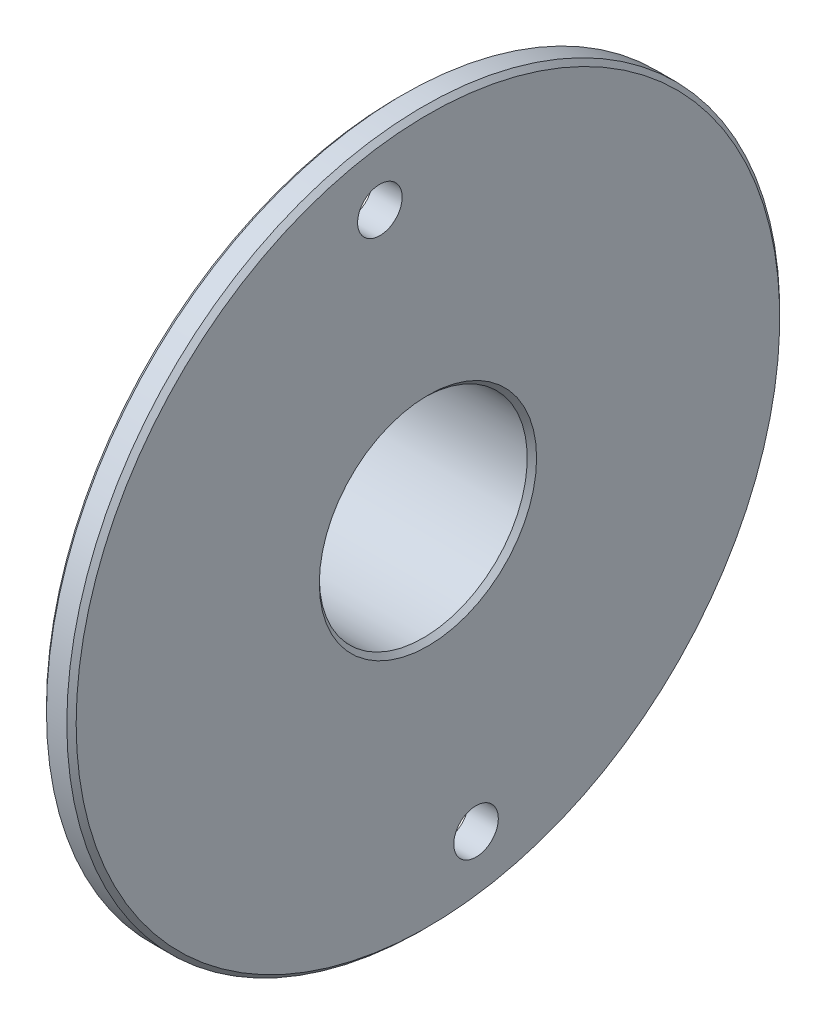
SolidWorks part; units mm, degrees
material "6061-T6 (SS)"
ref_plane "Front Plane" through (0, 0, 0) normal (0, 0, 1) x (1, 0, 0)
ref_plane "Top Plane" through (0, 0, 0) normal (0, 1, 0) x (1, 0, 0)
ref_plane "Right Plane" through (0, 0, 0) normal (1, 0, 0) x (0, 0, -1)
sketch "Sketch1" plane through (0, 0, 0) normal (0, 0, 1) x (1, 0, 0)
  line L0 (0, 0) -> (73.7918, 0) construction
  line L1 (0, 0) -> (-64.2399, 0) construction
  line L2 (-15.825, 13.7875) -> (-15.825, 11.6125)
  line L3 (-15.325, 14.2875) -> (0, 14.2875)
  line L4 (0, 14.2875) -> (0, 37.6)
  line L5 (0.5, 38.1) -> (2.675, 38.1)
  line L6 (3.175, 37.6) -> (3.175, 11.6125)
  line L7 (-15.325, 11.1125) -> (2.675, 11.1125)
  line L8 (0, 23.7294) -> (-10, 23.7294) construction
  line L9 (-10, 23.7294) -> (-13.175, 23.7294) construction
  line L10 (-15.325, 14.2875) -> (-15.825, 13.7875)
  line L11 (-15.825, 11.6125) -> (-15.325, 11.1125)
  line L12 (2.675, 11.1125) -> (3.175, 11.6125)
  line L13 (2.675, 38.1) -> (3.175, 37.6)
  line L14 (0, 37.6) -> (0.5, 38.1)
  point P3 (3.175, 11.1125)
  point P4 (-15.825, 14.2875)
  point P8 (0, 38.1)
  point P9 (3.175, 38.1)
  point P12 (-15.825, 11.1125)
  dimension "D2" = 3.175
  dimension "D3" = 28.575
  dimension "D4" = 22.225
  dimension "D5" = 19
  dimension "D6" = 10
  dimension "D7" = 3.175
  dimension "D8" = 76.2
revolve "Revolve1" add sketch "Sketch1" angle 360 about L0
sketch "Sketch2" plane through (3.175, 0, 0) normal (1, 0, 0) x (0, 0, -1)
  line L0 (0, 0) -> (-5.1393, 31.3313) construction
  circle A0 centre (-5.1393, 31.3313) radius 2.3812
  circle A2 centre (5.1393, -31.3313) radius 2.3813
  point P10 (0, 0)
  dimension "D1" = 4.7625
  dimension "D2" = 31.75
  dimension "D3" = 2
extrude "Cut-Extrude1" cut sketch "Sketch2" against normal blind 10
